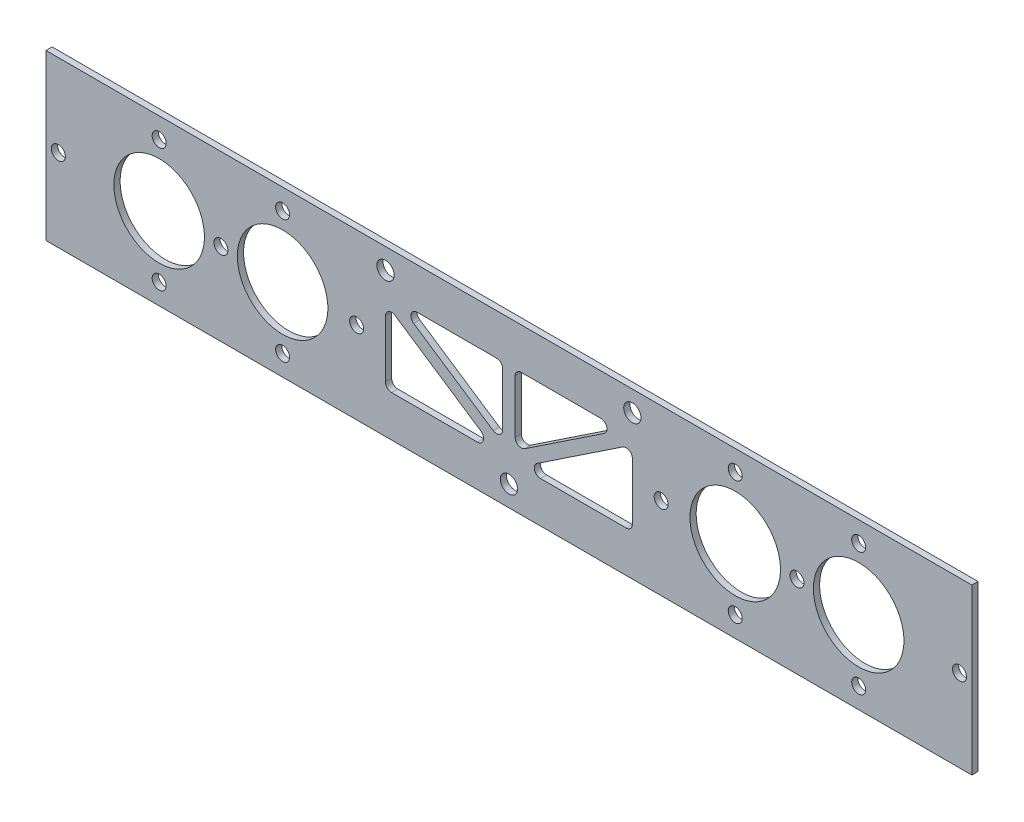
SolidWorks part; units mm, degrees
material "Thornel Mat VMA"
ref_plane "前视基准面" through (0, 0, 0) normal (0, 0, 1) x (1, 0, 0)
ref_plane "上视基准面" through (0, 0, 0) normal (0, 1, 0) x (1, 0, 0)
ref_plane "右视基准面" through (0, 0, 0) normal (1, 0, 0) x (0, 0, -1)
sketch "草图1" plane through (0, 0, 0) normal (0, 0, 1) x (1, 0, 0)
  line L1 (-112.5, 20) -> (112.5, 20)
  line L2 (-112.5, 20) -> (-112.5, -20)
  line L3 (-112.5, -20) -> (112.5, -20)
  line L4 (112.5, 20) -> (112.5, -20)
  line L5 (-112.5, 20) -> (112.5, -20) construction
  line L6 (-112.5, -20) -> (112.5, 20) construction
  point P0 (0, 0)
  dimension "D1" = 225
  dimension "D2" = 40
extrude "凸台-拉伸1" add sketch "草图1" along normal blind 1.5
sketch "草图2" plane through (0, 0, 0) normal (0, 0, -1) x (-1, 0, 0)
  line L6 (-6.8263, -7.2519) -> (-27.6679, 6.6425)
  line L7 (-28.5, -10) -> (-7.6583, -10)
  line L8 (-30, 5.3944) -> (-30, -8.5)
  line L12 (-1.5, -4.3944) -> (-1.5, 8.5)
  line L13 (-23.1737, 7.2519) -> (-3.8321, -5.6425)
  line L14 (-3, 10) -> (-22.3417, 10)
  line L18 (3.8321, -5.6425) -> (23.1737, 7.2519)
  line L19 (1.5, 8.5) -> (1.5, -4.3944)
  line L20 (22.3417, 10) -> (3, 10)
  line L24 (30, -8.5) -> (30, 5.3944)
  line L25 (7.6583, -10) -> (28.5, -10)
  line L26 (27.6679, 6.6425) -> (6.8263, -7.2519)
  arc A6 (-7.6583, -10) -> (-6.8263, -7.2519) centre (-7.6583, -8.5) ccw
  arc A7 (-30, -8.5) -> (-28.5, -10) centre (-28.5, -8.5) ccw
  arc A8 (-27.6679, 6.6425) -> (-30, 5.3944) centre (-28.5, 5.3944) ccw
  arc A12 (-3.8321, -5.6425) -> (-1.5, -4.3944) centre (-3, -4.3944) ccw
  arc A13 (-22.3417, 10) -> (-23.1737, 7.2519) centre (-22.3417, 8.5) ccw
  arc A14 (-1.5, 8.5) -> (-3, 10) centre (-3, 8.5) ccw
  arc A18 (1.5, -4.3944) -> (3.8321, -5.6425) centre (3, -4.3944) ccw
  arc A19 (3, 10) -> (1.5, 8.5) centre (3, 8.5) ccw
  arc A20 (23.1737, 7.2519) -> (22.3417, 10) centre (22.3417, 8.5) ccw
  circle A23 centre (85, 0) radius 11
  arc A24 (28.5, -10) -> (30, -8.5) centre (28.5, -8.5) ccw
  arc A25 (6.8263, -7.2519) -> (7.6583, -10) centre (7.6583, -8.5) ccw
  arc A26 (30, 5.3944) -> (27.6679, 6.6425) centre (28.5, 5.3944) ccw
  circle A28 centre (55, 0) radius 11
  circle A30 centre (30, 15) radius 2.1
  circle A32 centre (0, -15) radius 2.1
  circle A34 centre (-30, 15) radius 2.1
  circle A36 centre (-85, 0) radius 11
  circle A38 centre (-55, 0) radius 11
extrude "切除-拉伸1" cut sketch "草图2" against normal through all
sketch "草图3" plane through (0, 0, 0) normal (0, 0, -1) x (-1, 0, 0)
  line L3 (-23.1737, 7.2519) -> (-3.8321, -5.6425)
  line L4 (-3, 10) -> (-22.3417, 10)
  line L5 (-1.5, -4.3944) -> (-1.5, 8.5)
  line L6 (-23.1737, 7.2519) -> (-3.8321, -5.6425)
  line L7 (-3, 10) -> (-22.3417, 10)
  line L8 (-1.5, -4.3944) -> (-1.5, 8.5)
  line L9 (-30, 5.3944) -> (-30, -8.5)
  line L10 (-6.8263, -7.2519) -> (-27.6679, 6.6425)
  line L11 (-28.5, -10) -> (-7.6583, -10)
  line L12 (-30, 5.3944) -> (-30, -8.5)
  line L13 (-6.8263, -7.2519) -> (-27.6679, 6.6425)
  line L14 (-28.5, -10) -> (-7.6583, -10)
  line L15 (27.6679, 6.6425) -> (6.8263, -7.2519)
  line L16 (30, -8.5) -> (30, 5.3944)
  line L17 (7.6583, -10) -> (28.5, -10)
  line L18 (27.6679, 6.6425) -> (6.8263, -7.2519)
  line L19 (30, -8.5) -> (30, 5.3944)
  line L20 (7.6583, -10) -> (28.5, -10)
  line L21 (1.5, 8.5) -> (1.5, -4.3944)
  line L22 (22.3417, 10) -> (3, 10)
  line L23 (3.8321, -5.6425) -> (23.1737, 7.2519)
  line L24 (1.5, 8.5) -> (1.5, -4.3944)
  line L25 (22.3417, 10) -> (3, 10)
  line L26 (3.8321, -5.6425) -> (23.1737, 7.2519)
  circle A1 centre (85, 0) radius 11
  circle A2 centre (85, 0) radius 11
  circle A3 centre (55, 0) radius 11
  circle A4 centre (55, 0) radius 11
  circle A5 centre (0, -15) radius 2.1
  circle A6 centre (0, -15) radius 2.1
  arc A7 (-22.3417, 10) -> (-23.1737, 7.2519) centre (-22.3417, 8.5) ccw
  arc A8 (-1.5, 8.5) -> (-3, 10) centre (-3, 8.5) ccw
  arc A9 (-3.8321, -5.6425) -> (-1.5, -4.3944) centre (-3, -4.3944) ccw
  arc A10 (-22.3417, 10) -> (-23.1737, 7.2519) centre (-22.3417, 8.5) ccw
  arc A11 (-1.5, 8.5) -> (-3, 10) centre (-3, 8.5) ccw
  arc A12 (-3.8321, -5.6425) -> (-1.5, -4.3944) centre (-3, -4.3944) ccw
  circle A13 centre (-55, 0) radius 11
  circle A14 centre (-55, 0) radius 11
  circle A15 centre (30, 15) radius 2.1
  circle A16 centre (30, 15) radius 2.1
  arc A17 (-27.6679, 6.6425) -> (-30, 5.3944) centre (-28.5, 5.3944) ccw
  arc A18 (-7.6583, -10) -> (-6.8263, -7.2519) centre (-7.6583, -8.5) ccw
  arc A19 (-30, -8.5) -> (-28.5, -10) centre (-28.5, -8.5) ccw
  arc A20 (-27.6679, 6.6425) -> (-30, 5.3944) centre (-28.5, 5.3944) ccw
  arc A21 (-7.6583, -10) -> (-6.8263, -7.2519) centre (-7.6583, -8.5) ccw
  arc A22 (-30, -8.5) -> (-28.5, -10) centre (-28.5, -8.5) ccw
  circle A23 centre (-30, 15) radius 2.1
  circle A24 centre (-30, 15) radius 2.1
  arc A25 (30, 5.3944) -> (27.6679, 6.6425) centre (28.5, 5.3944) ccw
  arc A26 (28.5, -10) -> (30, -8.5) centre (28.5, -8.5) ccw
  arc A27 (6.8263, -7.2519) -> (7.6583, -10) centre (7.6583, -8.5) ccw
  arc A28 (30, 5.3944) -> (27.6679, 6.6425) centre (28.5, 5.3944) ccw
  arc A29 (28.5, -10) -> (30, -8.5) centre (28.5, -8.5) ccw
  arc A30 (6.8263, -7.2519) -> (7.6583, -10) centre (7.6583, -8.5) ccw
  arc A31 (3, 10) -> (1.5, 8.5) centre (3, 8.5) ccw
  arc A32 (23.1737, 7.2519) -> (22.3417, 10) centre (22.3417, 8.5) ccw
  arc A33 (1.5, -4.3944) -> (3.8321, -5.6425) centre (3, -4.3944) ccw
  arc A34 (3, 10) -> (1.5, 8.5) centre (3, 8.5) ccw
  arc A35 (23.1737, 7.2519) -> (22.3417, 10) centre (22.3417, 8.5) ccw
  arc A36 (1.5, -4.3944) -> (3.8321, -5.6425) centre (3, -4.3944) ccw
  circle A37 centre (-85, 0) radius 11
  circle A38 centre (-85, 0) radius 11
  circle A39 centre (55, -15) radius 1.7
  circle A40 centre (55, -15) radius 1.7
  circle A41 centre (85, -15) radius 1.7
  circle A42 centre (85, -15) radius 1.7
  circle A43 centre (-37, 0) radius 1.7
  circle A44 centre (-37, 0) radius 1.7
  circle A45 centre (37, 0) radius 1.7
  circle A46 centre (37, 0) radius 1.7
  circle A47 centre (70, 0) radius 1.7
  circle A48 centre (70, 0) radius 1.7
  circle A49 centre (-109.5, 0) radius 1.7
  circle A50 centre (-109.5, 0) radius 1.7
  circle A51 centre (-85, -15) radius 1.7
  circle A52 centre (-85, -15) radius 1.7
  circle A53 centre (109.5, 0) radius 1.7
  circle A54 centre (109.5, 0) radius 1.7
  circle A55 centre (-70, 0) radius 1.7
  circle A56 centre (-70, 0) radius 1.7
  circle A57 centre (-55, 15) radius 1.7
  circle A58 centre (-55, 15) radius 1.7
  circle A59 centre (85, 15) radius 1.7
  circle A60 centre (85, 15) radius 1.7
  circle A61 centre (-85, 15) radius 1.7
  circle A62 centre (-85, 15) radius 1.7
  circle A63 centre (-55, -15) radius 1.7
  circle A64 centre (-55, -15) radius 1.7
  circle A65 centre (55, 15) radius 1.7
  circle A66 centre (55, 15) radius 1.7
  dimension "D1" = 0
  dimension "D2" = 0
  dimension "D3" = 0
  dimension "D4" = 0
  dimension "D5" = 0
  dimension "D6" = 0
  dimension "D7" = 0
  dimension "D8" = 0
  dimension "D9" = 0
  dimension "D10" = 0
  dimension "D11" = 0
  dimension "D12" = 0
  dimension "D13" = 0
  dimension "D14" = 0
  dimension "D15" = 0
  dimension "D16" = 0
  dimension "D17" = 0
  dimension "D18" = 0
  dimension "D19" = 0
  dimension "D20" = 0
  dimension "D21" = 0
  dimension "D22" = 0
  dimension "D23" = 0
  dimension "D24" = 0
  dimension "D25" = 0
extrude "切除-拉伸2" cut sketch "草图3" against normal through all
